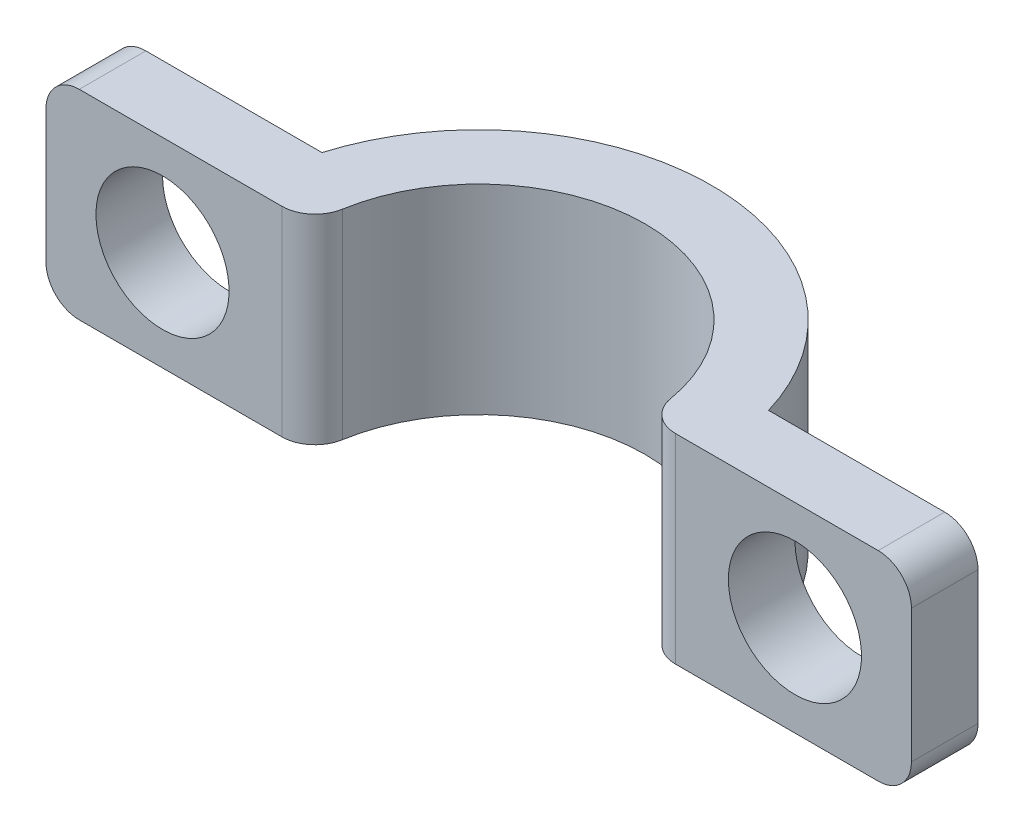
SolidWorks part; units mm, degrees
ref_plane "Front Plane" through (0, 0, 0) normal (0, 0, 1) x (1, 0, 0)
ref_plane "Top Plane" through (0, 0, 0) normal (0, 1, 0) x (1, 0, 0)
ref_plane "Right Plane" through (0, 0, 0) normal (1, 0, 0) x (0, 0, -1)
sketch "Sketch1" plane through (0, 0, 0) normal (0, 1, 0) x (1, 0, 0)
  line L0 (5, 0) -> (7, 0)
  line L1 (-5, 0) -> (-7, 0)
  arc A0 (5, 0) -> (-5, 0) centre (0, 0) ccw
  arc A1 (7, 0) -> (-7, 0) centre (0, 0) ccw
  dimension "D1" = 10
  dimension "D2" = 14
extrude "Boss-Extrude1" add sketch "Sketch1" along normal blind 6
sketch "Sketch2" plane through (0, 6, 0) normal (0, 1, 0) x (1, 0, 0)
  line L0 (7, 0) -> (13, 0)
  line L1 (13, 0) -> (13, 2)
  line L2 (13, 2) -> (6.7082, 2)
  line L3 (6.7082, 2) -> (7, 0)
  line L4 (0, -3.3) -> (0, 3.3) construction
  line L5 (-6.7082, 2) -> (-7, 0)
  line L6 (-13, 2) -> (-6.7082, 2)
  line L7 (-13, 0) -> (-13, 2)
  line L8 (-7, 0) -> (-13, 0)
  arc A0 (7, 0) -> (-7, 0) centre (0, 0) ccw construction
  dimension "D1" = 6
  dimension "D2" = 2
extrude "Boss-Extrude2" add sketch "Sketch2" against normal up to surface (6 mm away) up to face at (0, 0, -3)
sketch "Sketch3" plane through (0, 0, -2) normal (0, 0, -1) x (-1, 0, 0)
  line L0 (-13, 3) -> (-9.5, 3) construction
  line L1 (-13, 0) -> (-13, 6) construction
  line L2 (0, 3.3) -> (0, -3.3) construction
  circle A0 centre (-9.5, 3) radius 2
  circle A1 centre (9.5, 3) radius 2
  dimension "D2" = 4
  dimension "D1" = 3.5
extrude "Cut-Extrude1" cut sketch "Sketch3" against normal blind 6
fillet "Fillet1" radius 1 6 edges at (5, 3, 0) (-5, 3, 0) (-13, 0, -1) (13, 0, -1) (13, 6, -1) (-13, 6, -1)
